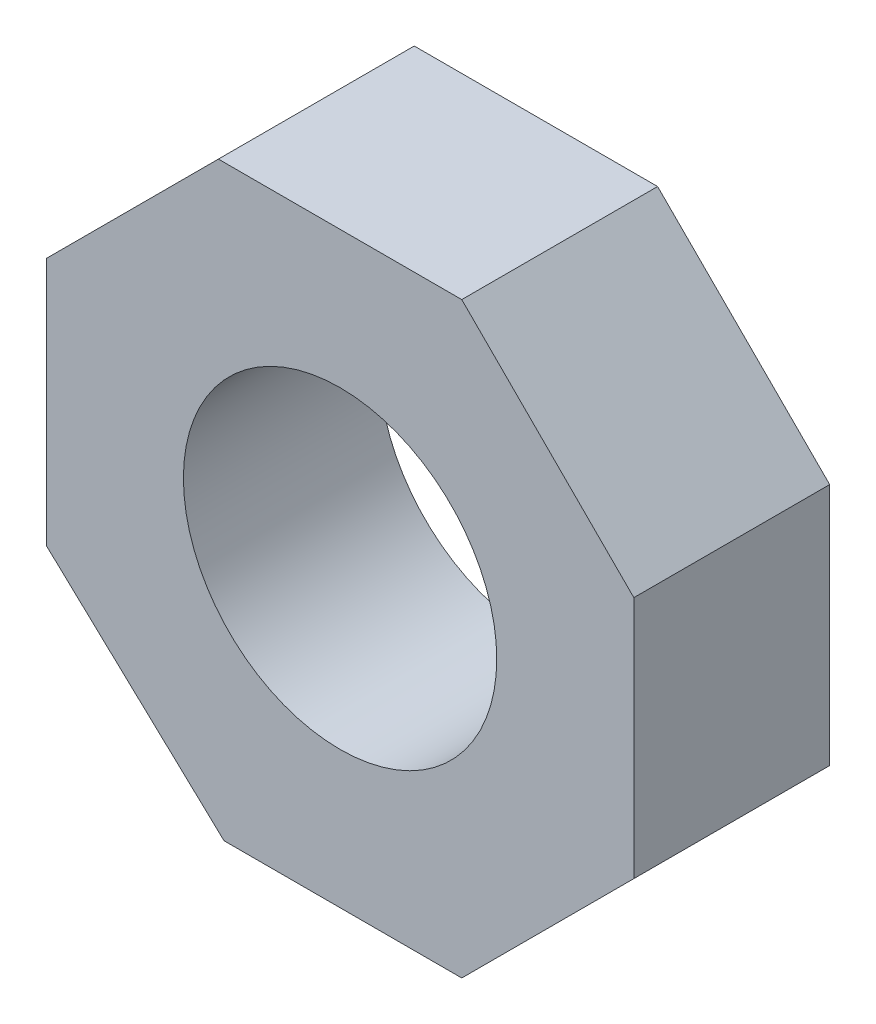
SolidWorks part; units mm, degrees
ref_plane "Plan de face" through (0, 0, 0) normal (0, 0, 1) x (1, 0, 0)
ref_plane "Plan de dessus" through (0, 0, 0) normal (0, 1, 0) x (1, 0, 0)
ref_plane "Plan de droite" through (0, 0, 0) normal (1, 0, 0) x (0, 0, -1)
sketch "Esquisse1" plane through (0, 0, 0) normal (0, 0, 1) x (1, 0, 0)
  line L0 (0, 0) -> (7.5, 0) construction
  line L1 (7.5, 0) -> (-7.5, 0) construction
  line L3 (7.5, 7.5) -> (7.5, -7.5) construction
  line L4 (-7.5, -7.5) -> (7.5, 7.5) construction
  line L5 (7.5, 7.5) -> (-7.5, 7.5) construction
  line L6 (0, 0) -> (0, 7.5) construction
  line L7 (0, 7.5) -> (0, -7.5) construction
  line L8 (7.5, -7.5) -> (-7.5, 7.5) construction
  line L9 (0, 0) -> (-5.3033, -5.3033) construction
  line L10 (-5.3033, -5.3033) -> (0, 0) construction
  line L11 (0, 0) -> (5.3033, -5.3033) construction
  line L12 (-7.5, 7.5) -> (0, 7.5) construction
  line L13 (0, 7.5) -> (7.5, 7.5) construction
  line L15 (7.5, -7.5) -> (-7.5, -7.5) construction
  line L16 (-7.5, -7.5) -> (-7.5, 7.5) construction
  line L17 (5.3033, -5.3033) -> (0, 0) construction
  line L18 (0, 0) -> (5.3033, 5.3033) construction
  line L19 (5.3033, 5.3033) -> (0, 0) construction
  line L20 (0, 0) -> (-5.3033, 5.3033) construction
  line L21 (5.3033, 5.3033) -> (3.1066, 7.5)
  line L22 (-7.5, 3.1066) -> (-5.3033, 5.3033)
  line L23 (-5.3033, 5.3033) -> (-3.1066, 7.5)
  line L24 (3.1066, 7.5) -> (7.5, 3.1066)
  line L25 (5.3033, -5.3033) -> (7.5, -3.1066)
  line L26 (7.5, -3.1066) -> (3.1066, -7.5)
  line L27 (-5.3033, -5.3033) -> (-2.9619, -7.5)
  line L28 (-2.9619, -7.5) -> (-7.5, -3.2423)
  line L29 (-7.5, -3.2423) -> (-7.5, 3.1066)
  line L30 (-3.1066, 7.5) -> (3.1066, 7.5)
  line L31 (7.5, 3.1066) -> (7.5, -3.1066)
  line L32 (7.5, -3.1066) -> (3.1066, -7.5)
  line L33 (-2.9619, -7.5) -> (3.1066, -7.5)
  circle A0 centre (0, 0) radius 7.5 construction
  circle A1 centre (0, 0) radius 4
extrude "Boss.-Extru.1" add sketch "Esquisse1" along normal blind 5 contours L27 L33 L26 L25 L31 L24 L21 L30 L23 L22 L29 L28 A1
